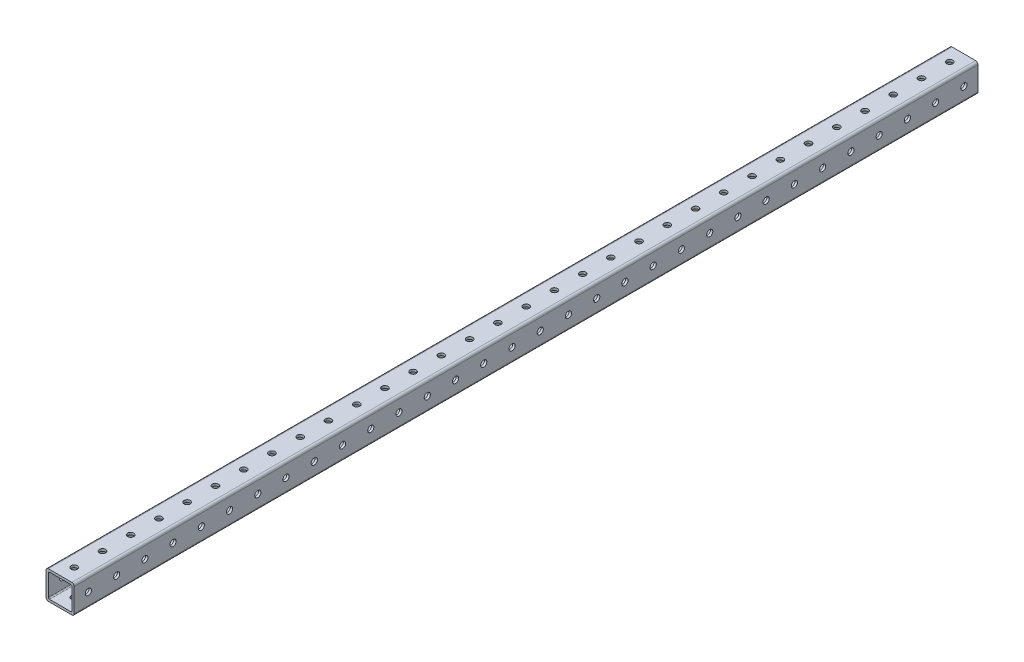
SolidWorks part; units mm, degrees
ref_plane "Front Plane" through (0, 0, 0) normal (0, 0, 1) x (1, 0, 0)
ref_plane "Top Plane" through (0, 0, 0) normal (0, 1, 0) x (1, 0, 0)
ref_plane "Right Plane" through (0, 0, 0) normal (1, 0, 0) x (0, 0, -1)
sketch "Sketch1" plane through (0, 0, 0) normal (0, 0, 1) x (1, 0, 0)
  line L0 (-19.05, -19.05) -> (19.05, 19.05) construction
  line L1 (-15.875, 19.05) -> (15.875, 19.05)
  line L2 (-19.05, 15.875) -> (-19.05, -15.875)
  line L3 (-15.875, -19.05) -> (15.875, -19.05)
  line L4 (19.05, 15.875) -> (19.05, -15.875)
  arc A0 (15.875, 19.05) -> (19.05, 15.875) centre (15.875, 15.875) cw
  arc A1 (15.875, -19.05) -> (19.05, -15.875) centre (15.875, -15.875) ccw
  arc A2 (-19.05, -15.875) -> (-15.875, -19.05) centre (-15.875, -15.875) ccw
  arc A3 (-15.875, 19.05) -> (-19.05, 15.875) centre (-15.875, 15.875) ccw
  dimension "D1" = 3.175
  dimension "D2" = 38.1
extrude "Extrude-Thin1" add sketch "Sketch1" along normal mid plane 1219.2 thin
fillet "Fillet1" radius 1.6002 4 edges at (15.875, -15.875, 0) (15.875, 15.875, 0) (-15.875, 15.875, 0) (-15.875, -15.875, 0)
sketch "Sketch2" plane through (0, 0, 0) normal (0, 1, 0) x (1, 0, 0)
  line L0 (14.2748, -609.6) -> (-14.2748, -609.6) construction
  line L1 (0, -590.55) -> (0, -552.45) construction
  circle A0 centre (0, -590.55) radius 4.1656
  point P2 (0, -609.6)
  dimension "Bolt Hole" = 8.3312
  dimension "1/2 of Center to Center" = 19.05
  dimension "Center to Center" = 38.1
extrude "Cut-Extrude1" cut sketch "Sketch2" against normal through all and the other way through all
ref_axis "Axis1" through (0, 0, 590.55) along (0, 0, -1)
pattern_linear "LPattern1" count 32 spacing 38.1 along (0, 0, -1) of "Cut-Extrude1"
pattern_circular "CirPattern1" count 2 over 90 about axis through (0, 0, 590.55) along (0, 0, -1) of "LPattern1", "Cut-Extrude1"
equation "\"1/2 of Center to Center@Sketch2\" = \"Center to Center@Sketch2\"/2"
equation "\"D1@LPattern1\" = \"Length@Extrude-Thin1\"/\"Center to Center@Sketch2\""
equation "\"D3@LPattern1\" = \"Center to Center@Sketch2\""
